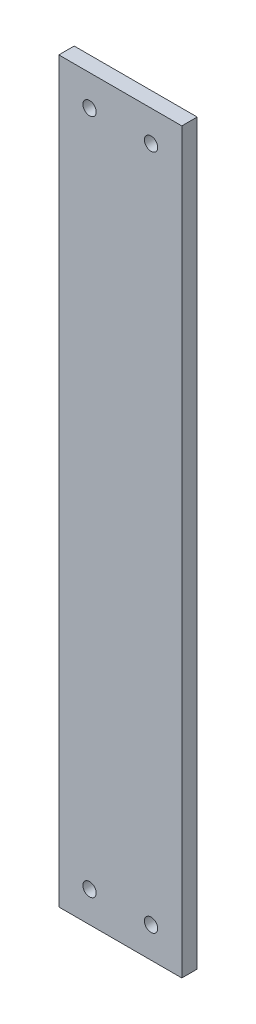
SolidWorks part; units mm, degrees
material "Pin"
ref_plane "Front" through (0, 0, 0) normal (0, 0, 1) x (1, 0, 0)
ref_plane "Top" through (0, 0, 0) normal (0, 1, 0) x (1, 0, 0)
ref_plane "Right" through (0, 0, 0) normal (1, 0, 0) x (0, 0, -1)
sketch "Esquisse1" plane through (0, 0, 0) normal (0, 0, 1) x (1, 0, 0)
  line L1 (-25.4, 152.4) -> (25.4, 152.4)
  line L2 (-25.4, 152.4) -> (-25.4, -152.4)
  line L3 (-25.4, -152.4) -> (25.4, -152.4)
  line L4 (25.4, 152.4) -> (25.4, -152.4)
  line L5 (-25.4, 152.4) -> (25.4, -152.4) construction
  line L6 (-25.4, -152.4) -> (25.4, 152.4) construction
  point P0 (0, 0)
  dimension "D1" = 304.8
  dimension "D2" = 50.8
extrude "Boss.-Extru.1" add sketch "Esquisse1" along normal blind 6.35
sketch "Esquisse2" plane through (0, 0, 6.35) normal (0, 0, 1) x (1, 0, 0)
  line L0 (25.4, 152.4) -> (-25.4, 152.4) construction
  line L2 (25.4, -152.4) -> (25.4, 152.4) construction
  line L3 (-25.4, 152.4) -> (-25.4, -152.4) construction
  line L4 (50, 0) -> (-50, 0) construction
  circle A0 centre (12.7, 139.7) radius 2.75
  circle A1 centre (-12.7, 139.7) radius 2.75
  circle A2 centre (12.7, -139.7) radius 2.75
  circle A3 centre (-12.7, -139.7) radius 2.75
  dimension "D1" = 5.5
  dimension "D2" = 5.5
  dimension "D3" = 12.7
  dimension "D4" = 12.7
  dimension "D5" = 12.7
  dimension "D6" = 12.7
extrude "Enlèv. mat.-Extru.1" cut sketch "Esquisse2" against normal through all
